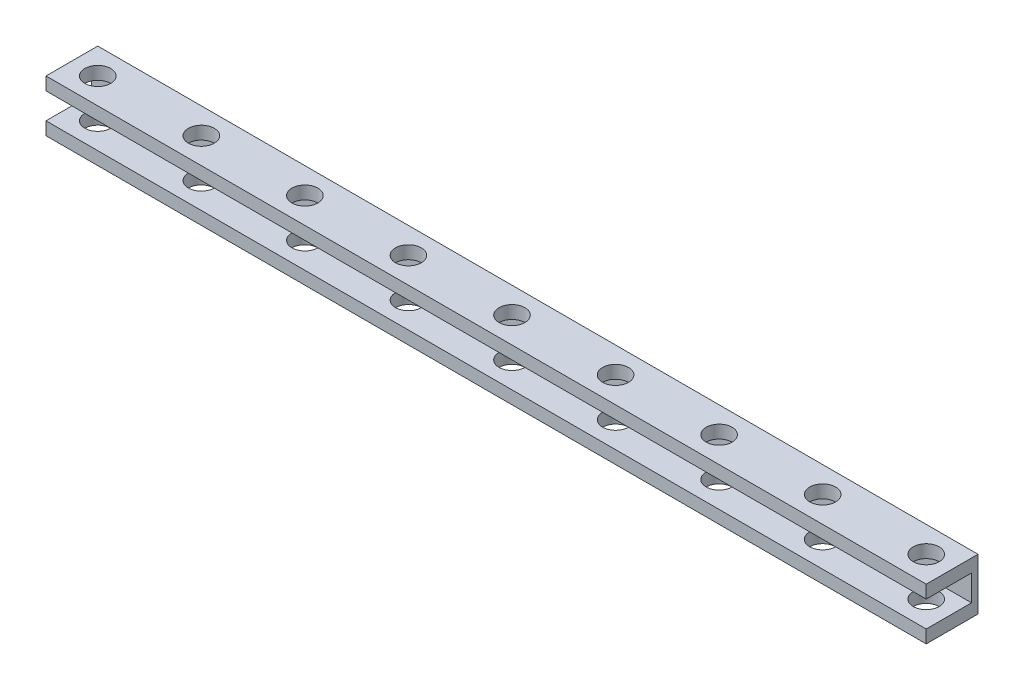
SolidWorks part; units mm, degrees
material "6061 Alloy"
ref_plane "前视基准面" through (0, 0, 0) normal (0, 0, 1) x (1, 0, 0)
ref_plane "上视基准面" through (0, 0, 0) normal (0, 1, 0) x (1, 0, 0)
ref_plane "右视基准面" through (0, 0, 0) normal (1, 0, 0) x (0, 0, -1)
other "Configuration Table"
sketch "Sketch1" plane through (0, 0, 0) normal (0, 1, 0) x (1, 0, 0)
  line L1 (-69.6967, 32.4399) -> (66.3033, 32.4399)
  line L2 (-69.6967, 32.4399) -> (-69.6967, 24.4399)
  line L3 (-69.6967, 24.4399) -> (66.3033, 24.4399)
  line L4 (66.3033, 32.4399) -> (66.3033, 24.4399)
  dimension "D1" = 136
  dimension "D2" = 8
extrude "Boss-Extrude1" add sketch "Sketch1" along normal blind 8
sketch "Sketch2" plane through (-69.6967, 0, 0) normal (-1, 0, 0) x (0, 0, 1)
  line L0 (-24.4399, 8) -> (-24.4399, 0) construction
  line L1 (-31.4399, 6) -> (-24.4399, 6)
  line L2 (-31.4399, 6) -> (-31.4399, 2)
  line L3 (-31.4399, 2) -> (-24.4399, 2)
  line L4 (-24.4399, 6) -> (-24.4399, 2)
  line L5 (-32.4399, 8) -> (-24.4399, 8) construction
  line L6 (-32.4399, 0) -> (-24.4399, 0) construction
  line L7 (-32.4399, 8) -> (-32.4399, 0) construction
  dimension "D1" = 2
  dimension "D2" = 2
  dimension "D3" = 1
extrude "Cut-Extrude1" cut sketch "Sketch2" against normal blind 142
sketch "Sketch3" plane through (0, 8, 0) normal (0, 1, 0) x (1, 0, 0)
  line L0 (-69.6967, 32.4399) -> (-69.6967, 24.4399) construction
  line L1 (-69.6967, 24.4399) -> (66.3033, 24.4399) construction
  circle A0 centre (-65.6967, 28.4399) radius 2
  circle A1 centre (-49.6967, 28.4399) radius 2
  circle A2 centre (-33.6967, 28.4399) radius 2
  circle A3 centre (-17.6967, 28.4399) radius 2
  circle A4 centre (-1.6967, 28.4399) radius 2
  circle A5 centre (14.3033, 28.4399) radius 2
  circle A6 centre (30.3033, 28.4399) radius 2
  circle A7 centre (46.3033, 28.4399) radius 2
  circle A8 centre (62.3033, 28.4399) radius 2
  dimension "D1" = 16
  dimension "D5" = 16
  dimension "D10" = 16
  dimension "D2" = 16
  dimension "D3" = 4
  dimension "D4" = 4
  dimension "D6" = 16
  dimension "D7" = 16
  dimension "D8" = 16
  dimension "D9" = 16
extrude "Cut-Extrude2" cut sketch "Sketch3" against normal blind 142
